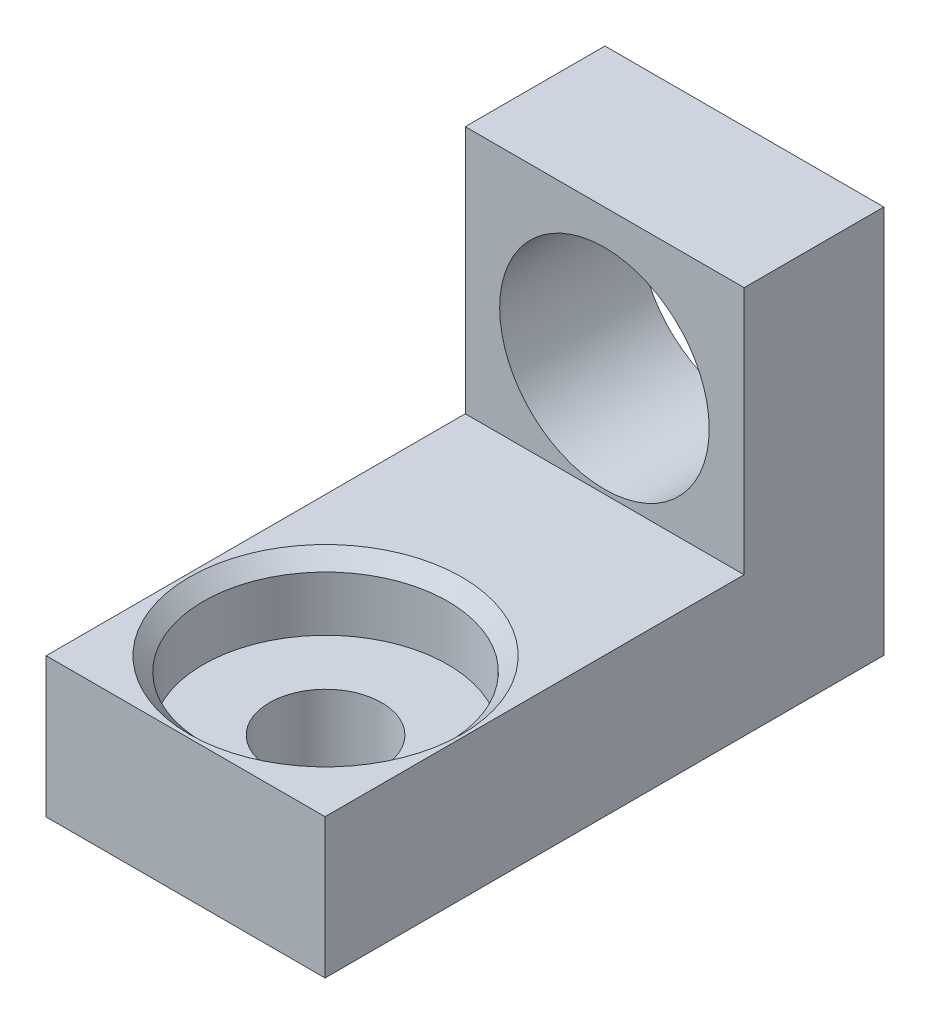
SolidWorks part; units mm, degrees
ref_plane "Front Plane" through (0, 0, 0) normal (0, 0, 1) x (1, 0, 0)
ref_plane "Top Plane" through (0, 0, 0) normal (0, 1, 0) x (1, 0, 0)
ref_plane "Right Plane" through (0, 0, 0) normal (1, 0, 0) x (0, 0, -1)
sketch "Sketch1" plane through (0, 0, 0) normal (0, 0, 1) x (1, 0, 0)
  line L0 (-6.3269, 0) -> (-6.3269, -11.303)
  line L1 (-6.3269, -11.303) -> (6.35, -11.303)
  line L2 (6.35, -11.303) -> (6.35, 0)
  line L3 (-6.3269, 0) -> (-6.3269, 6.35)
  line L4 (-6.3269, 6.35) -> (6.35, 6.35)
  line L5 (6.35, 6.35) -> (6.35, 0)
  circle A1 centre (0, 0) radius 4.7625
  dimension "D1" = 6.35
  dimension "D2" = 9.525
  dimension "D3" = 11.303
extrude "Boss-Extrude1" add sketch "Sketch1" along normal blind 6.35
sketch "Sketch2" plane through (0, 0, 6.35) normal (0, 0, 1) x (1, 0, 0)
  line L0 (6.35, -11.303) -> (6.35, 6.35) construction
  line L1 (-6.3269, -11.303) -> (6.35, -11.303)
  line L2 (-6.3269, -11.303) -> (-6.3269, -4.953)
  line L3 (-6.3269, -4.953) -> (6.35, -4.953)
  line L4 (6.35, -11.303) -> (6.35, -4.953)
  dimension "D1" = 6.35
extrude "Boss-Extrude2" add sketch "Sketch2" along normal blind 19.05
sketch "Sketch3" plane through (0, -4.953, 0) normal (0, 1, 0) x (1, 0, 0)
  line L0 (-6.3269, -25.4) -> (-6.3269, -6.35) construction
  line L1 (6.35, -25.4) -> (-6.3269, -25.4) construction
  circle A0 centre (0.0231, -19.05) radius 3.175
  dimension "D1" = 6.35
  dimension "D2" = 6.35
  dimension "D3" = 6.35
hole_wizard "CBORE for #10 Binding Head Machine Screw1" positions "Sketch6" profile "Sketch7" counterbore size "#10" standard "ANSI Inch" end condition through all
sketch "Sketch6" plane through (0, -4.953, 0) normal (0, 1, 0) x (1, 0, 0)
  point P0 (0.0231, -19.05)
sketch "Sketch7" plane through (0.0231, -4.953, 19.05) normal (1, 0, 0) x (0, 0, 1)
  line L0 (0, 0) -> (0, 6.35)
  line L1 (0, 6.35) -> (2.5527, 6.35)
  line L3 (2.5527, 6.35) -> (2.5527, 3.1242)
  line L4 (5.5562, 3.1242) -> (2.5527, 3.1242)
  line L5 (5.5562, 3.1242) -> (5.5562, 0.635)
  line L6 (5.5562, 0.635) -> (6.1913, 0)
  line L7 (6.1913, 0) -> (0, 0)
  line L8 (-5.5562, 0.635) -> (-6.1913, 0) construction
  line L11 (0, -6.35) -> (0, 107.95) construction
  dimension "Thru Hole Dia." = 5.1054
  dimension "Thru Hole Depth" = 6.35
  dimension "C'Bore Dia." = 11.1125
  dimension "C'Bore Depth" = 3.1242
  dimension "Near C'Sink Dia." = 12.3825
  dimension "Near C'Sink Angle" = 90
